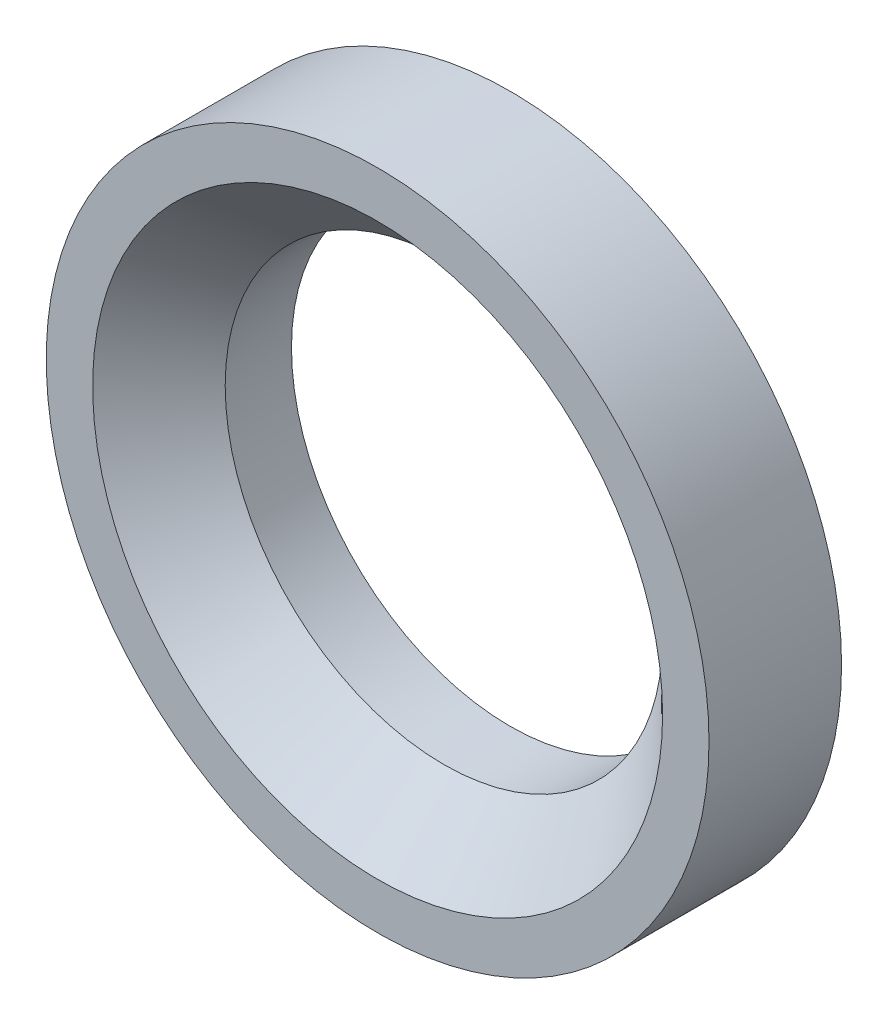
SolidWorks part; units mm, degrees
ref_plane "Front" through (0, 0, 0) normal (0, 0, 1) x (1, 0, 0)
ref_plane "Top" through (0, 0, 0) normal (0, 1, 0) x (1, 0, 0)
ref_plane "Right" through (0, 0, 0) normal (1, 0, 0) x (0, 0, -1)
sketch "Sketch1" plane through (0, 0, 0) normal (0, 0, 1) x (1, 0, 0)
  circle A0 centre (0, 0) radius 4.191
  circle A2 centre (0, 0) radius 6.35
  dimension "D1" = 8.382
  dimension "D2" = 12.7
extrude "Boss-Extrude1" add sketch "Sketch1" along normal blind 2.54
chamfer "Chamfer1" distance 1.27 angle 45 1 edges at (4.191, 0, 2.54)
